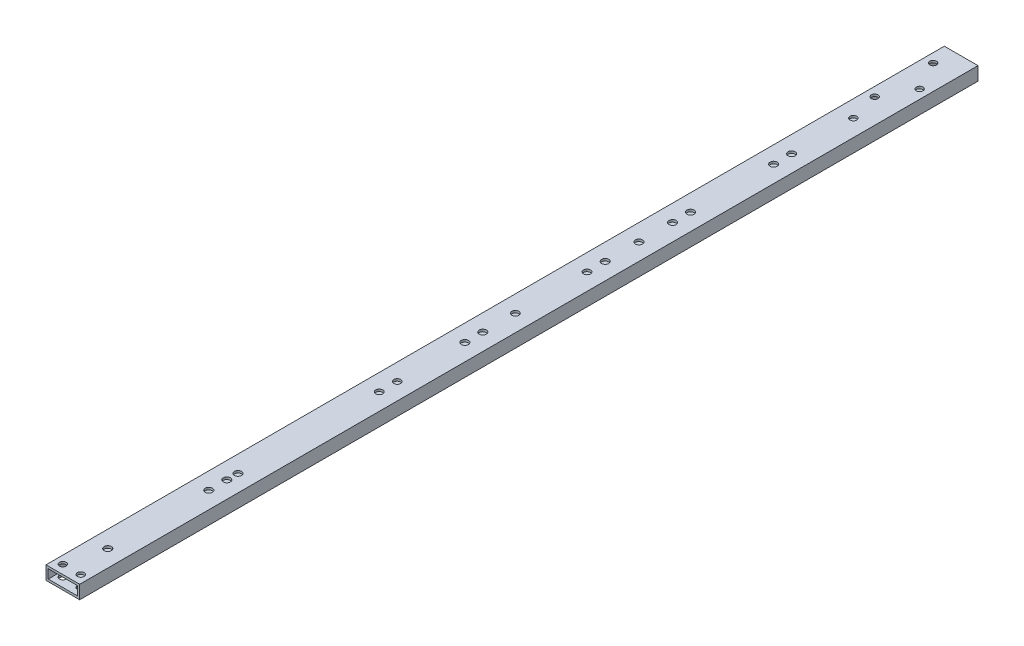
SolidWorks part; units mm, degrees
material "6061 合金"
ref_plane "前视基准面" through (0, 0, 0) normal (0, 0, 1) x (1, 0, 0)
ref_plane "上视基准面" through (0, 0, 0) normal (0, 1, 0) x (1, 0, 0)
ref_plane "右视基准面" through (0, 0, 0) normal (1, 0, 0) x (0, 0, -1)
sketch "草图1" plane through (0, 0, 0) normal (0, 0, 1) x (1, 0, 0)
  line L1 (7.5, -3) -> (-7.5, -3)
  line L2 (7.5, -3) -> (7.5, 3)
  line L3 (7.5, 3) -> (-7.5, 3)
  line L4 (-7.5, -3) -> (-7.5, 3)
  line L5 (7.5, -3) -> (-7.5, 3) construction
  line L6 (7.5, 3) -> (-7.5, -3) construction
  line L7 (6.5, -2) -> (-6.5, -2)
  line L8 (6.5, -2) -> (6.5, 2)
  line L9 (6.5, 2) -> (-6.5, 2)
  line L10 (-6.5, -2) -> (-6.5, 2)
  line L11 (6.5, -2) -> (-6.5, 2) construction
  line L12 (6.5, 2) -> (-6.5, -2) construction
  point P0 (0, 0)
  point P6 (0, 0)
  dimension "D1" = 6
  dimension "D2" = 15
  dimension "D3" = 1
  dimension "D4" = 1
extrude "凸台-拉伸1" add sketch "草图1" along normal blind 400
sketch "草图2" plane through (0, -3, 0) normal (0, -1, 0) x (1, 0, 0)
  line L0 (-3.5, 0) -> (-3.5, 35) construction
  line L1 (-7.5, 0) -> (7.5, 0) construction
  line L3 (3.5, 22) -> (12.9435, 22) construction
  line L4 (-7.5, 400) -> (-7.5, 0) construction
  line L5 (7.5, 400) -> (7.5, 0) construction
  circle A0 centre (-3.5, 35) radius 1.5
  circle A1 centre (-3.5, 9) radius 1.5
  circle A2 centre (3.5, 22) radius 1.5
  circle A3 centre (0, 48) radius 1.5
  dimension "D2" = 3
  dimension "D6" = 13
  dimension "D1" = 26
  dimension "D3" = 22
  dimension "D4" = 4
  dimension "D5" = 4
  dimension "D7" = 3.5
extrude "切除-拉伸1" cut sketch "草图2" against normal blind 10
sketch "草图3" plane through (0, 3, 0) normal (0, 1, 0) x (1, 0, 0)
  circle A0 centre (0, -322) radius 1.6 construction
  circle A1 centre (0, -327) radius 1.6 construction
  circle A2 centre (0, -335) radius 1.6 construction
  circle A3 centre (0, -380) radius 1.6 construction
  circle A4 centre (0, -322) radius 1.6
  circle A5 centre (0, -327) radius 1.6
  circle A6 centre (0, -335) radius 1.6
  circle A7 centre (0, -380) radius 1.6
  circle A8 centre (0, -213) radius 1.6 construction
  circle A9 centre (0, -221) radius 1.6 construction
  circle A10 centre (0, -213) radius 1.6
  circle A11 centre (0, -221) radius 1.6
  circle A12 centre (0, -198.5) radius 1.55 construction
  circle A13 centre (0, -158.5) radius 1.6 construction
  circle A14 centre (0, -198.5) radius 1.55
  circle A15 centre (0, -158.5) radius 1.6
  circle A16 centre (0, -143.5) radius 1.6 construction
  circle A17 centre (0, -143.5) radius 1.6
  circle A18 centre (0, -128.5) radius 1.6 construction
  circle A19 centre (0, -120.5) radius 1.6 construction
  circle A20 centre (0, -128.5) radius 1.6
  circle A21 centre (0, -120.5) radius 1.6
  circle A22 centre (0, -75.5) radius 1.6 construction
  circle A23 centre (0, -83.5) radius 1.6 construction
  circle A24 centre (0, -75.5) radius 1.6
  circle A25 centre (0, -83.5) radius 1.6
extrude "切除-拉伸2" cut sketch "草图3" against normal blind 10
sketch "草图4" plane through (0, 3, 0) normal (0, 1, 0) x (1, 0, 0)
  circle A0 centre (0, -251.1) radius 1.55 construction
  circle A1 centre (0, -259.1) radius 1.55 construction
  circle A2 centre (0, -251.1) radius 1.55
  circle A3 centre (0, -259.1) radius 1.55
  circle A4 centre (0, -166.6) radius 1.55 construction
  circle A5 centre (0, -166.6) radius 1.55
  circle A6 centre (-4, -396) radius 1.5 construction
  circle A7 centre (4, -396) radius 1.5 construction
  circle A8 centre (-4, -396) radius 1.5
  circle A9 centre (4, -396) radius 1.5
extrude "切除-拉伸3" cut sketch "草图4" against normal through all
